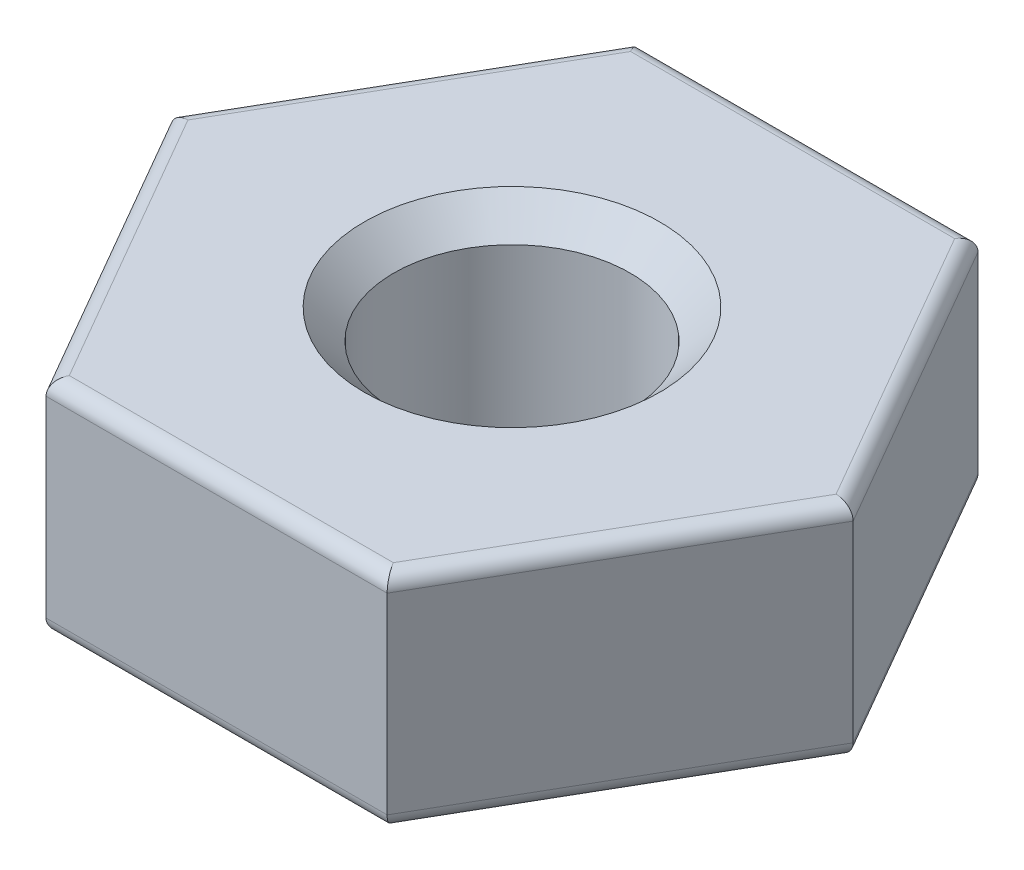
SolidWorks part; units mm, degrees
material "6061 Alloy"
ref_plane "Front Plane" through (0, 0, 0) normal (0, 0, 1) x (1, 0, 0)
ref_plane "Top Plane" through (0, 0, 0) normal (0, 1, 0) x (1, 0, 0)
ref_plane "Right Plane" through (0, 0, 0) normal (1, 0, 0) x (0, 0, -1)
sketch "Sketch1" plane through (0, 0, 0) normal (0, 1, 0) x (1, 0, 0)
  line L1 (2.3094, 0) -> (1.1547, 2)
  line L2 (1.1547, 2) -> (-1.1547, 2)
  line L3 (-1.1547, 2) -> (-2.3094, 0)
  line L4 (-2.3094, 0) -> (-1.1547, -2)
  line L5 (-1.1547, -2) -> (1.1547, -2)
  line L6 (1.1547, -2) -> (2.3094, 0)
  circle A0 centre (0, 0) radius 2 construction
  dimension "D1" = 4
extrude "Boss-Extrude1" add sketch "Sketch1" along normal blind 1.5
fillet "Fillet2" radius 0.1 12 edges at (-1.7321, 1.5, -1) (0, 1.5, -2) (1.7321, 1.5, -1) (1.7321, 1.5, 1) (0, 1.5, 2) (-1.7321, 1.5, 1) (1.7321, 0, 1) (1.7321, 0, -1) (0, 0, -2) (-1.7321, 0, -1) (-1.7321, 0, 1) (0, 0, 2)
sketch "Sketch2" plane through (0, 1.5, 0) normal (0, 1, 0) x (1, 0, 0)
  point P0 (0, 0)
hole_wizard "M2x0.4 Tapped Hole1" positions "Sketch2" profile "Sketch3" tap size "M2x0.4" standard "ANSI Metric" end condition through all
sketch "Sketch3" plane through (0, 1.5, 0) normal (1, 0, 0) x (0, 0, 1)
  line L0 (0, 0) -> (0, 1.5)
  line L1 (0, 1.5) -> (0.825, 1.5)
  line L2 (0.8, 1.475) -> (0.8, 0.2)
  line L3 (0.8, 0.2) -> (1, 0)
  line L5 (1, 0) -> (0, 0)
  line L6 (-0.8, 0.2) -> (-1, 0) construction
  line L7 (0.825, 1.5) -> (0.8, 1.475)
  line L8 (-0.825, 1.5) -> (-0.8, 1.475) construction
  line L11 (0, -6.35) -> (0, 107.95) construction
  dimension "Thru Tap Drill Dia." = 1.6
  dimension "Thru Tap Drill Depth" = 1.5
  dimension "Near C'Sink Dia." = 2
  dimension "Near C'Sink Angle" = 90
  dimension "Far C'Sink Dia." = 1.65
  dimension "Far C'Sink Angle" = 90
cosmetic thread "Hole Thread2" parameters "D2"=2
